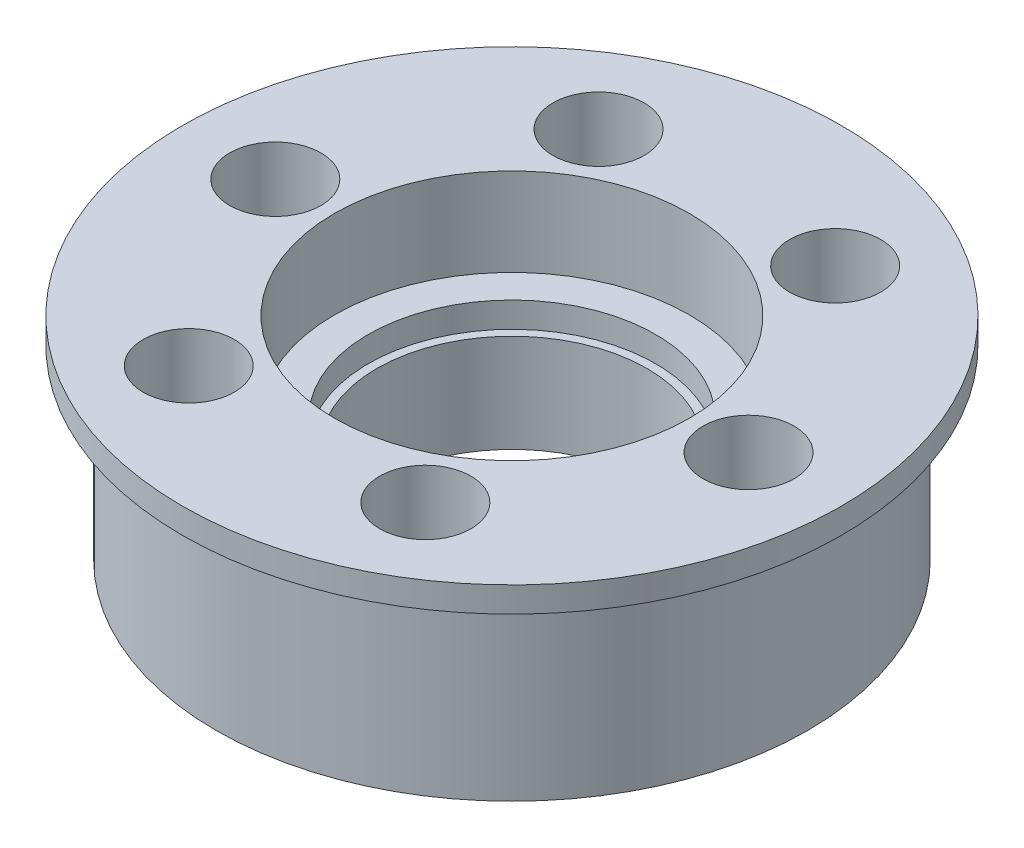
SolidWorks part; units mm, degrees
ref_plane "Front Plane" through (0, 0, 0) normal (0, 0, 1) x (1, 0, 0)
ref_plane "Top Plane" through (0, 0, 0) normal (0, 1, 0) x (1, 0, 0)
ref_plane "Right Plane" through (0, 0, 0) normal (1, 0, 0) x (0, 0, -1)
sketch "Sketch1" plane through (0, 0, 0) normal (0, 1, 0) x (1, 0, 0)
  circle A0 centre (0, 0) radius 17.5
  dimension "D1" = 35
extrude "Boss-Extrude1" add sketch "Sketch1" along normal blind 11
sketch "Sketch2" plane through (0, 11, 0) normal (0, 1, 0) x (1, 0, 0)
  circle A0 centre (0, 0) radius 19.5
  dimension "D1" = 39
extrude "Boss-Extrude2" add sketch "Sketch2" along normal blind 1.5
sketch "Sketch3" plane through (0, 12.5, 0) normal (0, 1, 0) x (1, 0, 0)
  circle A0 centre (0, 0) radius 10.5
  dimension "D1" = 21
extrude "Cut-Extrude1" cut sketch "Sketch3" against normal blind 5.2
sketch "Sketch4" plane through (0, 7.3, 0) normal (0, 1, 0) x (1, 0, 0)
  circle A3 centre (0, 0) radius 8.5
  circle A4 centre (0, 0) radius 8.5
  dimension "D1" = 2
extrude "Cut-Extrude2" cut sketch "Sketch4" against normal blind 1.5
sketch "Sketch7" plane through (0, 0, 0) normal (0, -1, 0) x (1, 0, 0)
  circle A1 centre (0, 0) radius 8
  dimension "D1" = 16
extrude "Cut-Extrude4" cut sketch "Sketch7" against normal up to next
sketch "Sketch9" plane through (0, 0, 0) normal (0, -1, 0) x (1, 0, 0)
  line L0 (0, 0) -> (0, 8) construction
  line L1 (0, 8) -> (0, 17.5) construction
  circle A0 centre (0, 0) radius 8 construction
  circle A1 centre (0, 0) radius 17.5 construction
  circle A2 centre (0, 12.75) radius 2.7
  circle A3 centre (11.0418, 6.375) radius 2.7
  circle A4 centre (11.0418, -6.375) radius 2.7
  circle A5 centre (0, -12.75) radius 2.7
  circle A6 centre (-11.0418, -6.375) radius 2.7
  circle A7 centre (-11.0418, 6.375) radius 2.7
  point P25 (0, 0)
  dimension "D1" = 5.4
  dimension "D2" = 6
extrude "Cut-Extrude5" cut sketch "Sketch9" against normal blind 6
sketch "Sketch10" plane through (0, 12.5, 0) normal (0, 1, 0) x (1, 0, 0)
  circle A0 centre (0, 0) radius 14 construction
  circle A1 centre (14, 0) radius 2.7
  circle A2 centre (7, -12.1244) radius 2.7
  circle A3 centre (-7, -12.1244) radius 2.7
  circle A4 centre (-14, 0) radius 2.7
  circle A5 centre (-7, 12.1244) radius 2.7
  circle A6 centre (7, 12.1244) radius 2.7
  point P17 (0, 0)
  dimension "D1" = 5.4
  dimension "D2" = 28
  dimension "D3" = 6
extrude "Cut-Extrude6" cut sketch "Sketch10" against normal blind 6.5
